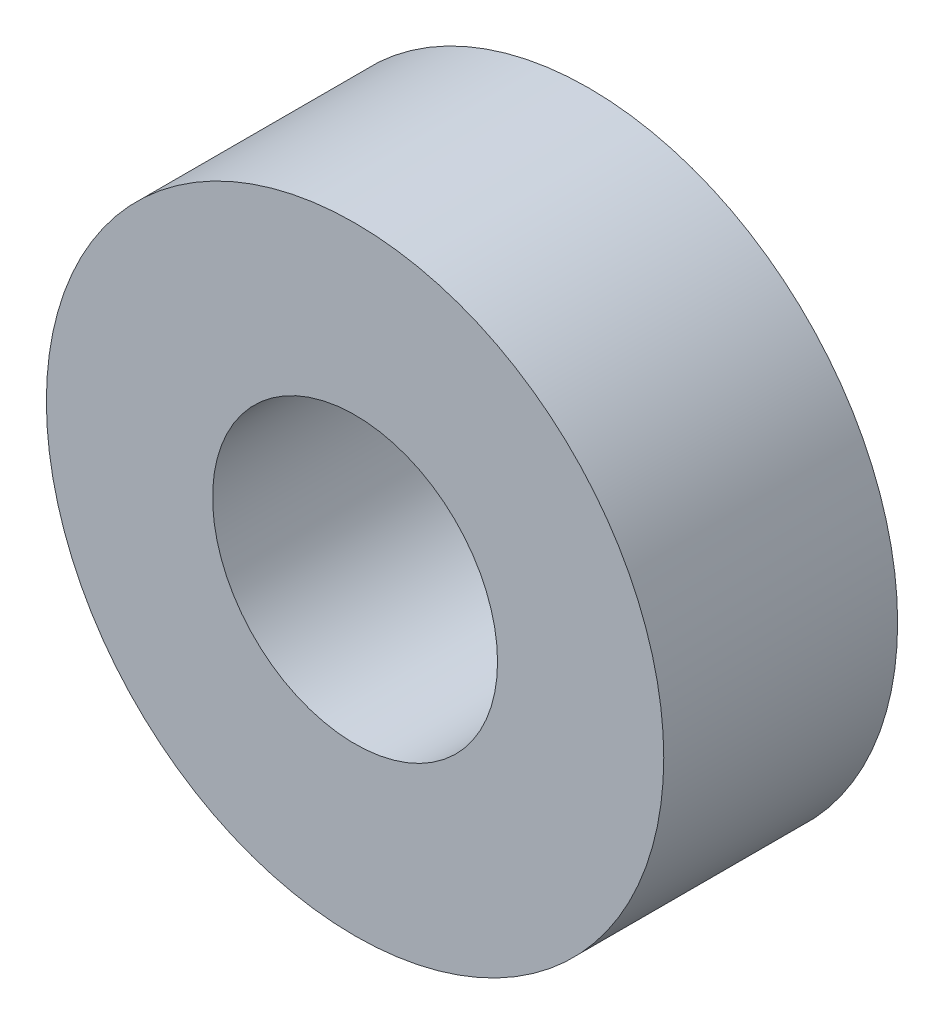
SolidWorks part; units mm, degrees
material "Chrome Stainless Steel"
ref_plane "Front Plane" through (0, 0, 0) normal (0, 0, 1) x (1, 0, 0)
ref_plane "Top Plane" through (0, 0, 0) normal (0, 1, 0) x (1, 0, 0)
ref_plane "Right Plane" through (0, 0, 0) normal (1, 0, 0) x (0, 0, -1)
sketch "Sketch1" plane through (0, 0, 0) normal (0, 0, 1) x (1, 0, 0)
  circle A0 centre (0, 0) radius 3.0462
  circle A1 centre (0, 0) radius 6.6
  dimension "D1" = 13.2
extrude "Boss-Extrude1" add sketch "Sketch1" along normal blind 5
